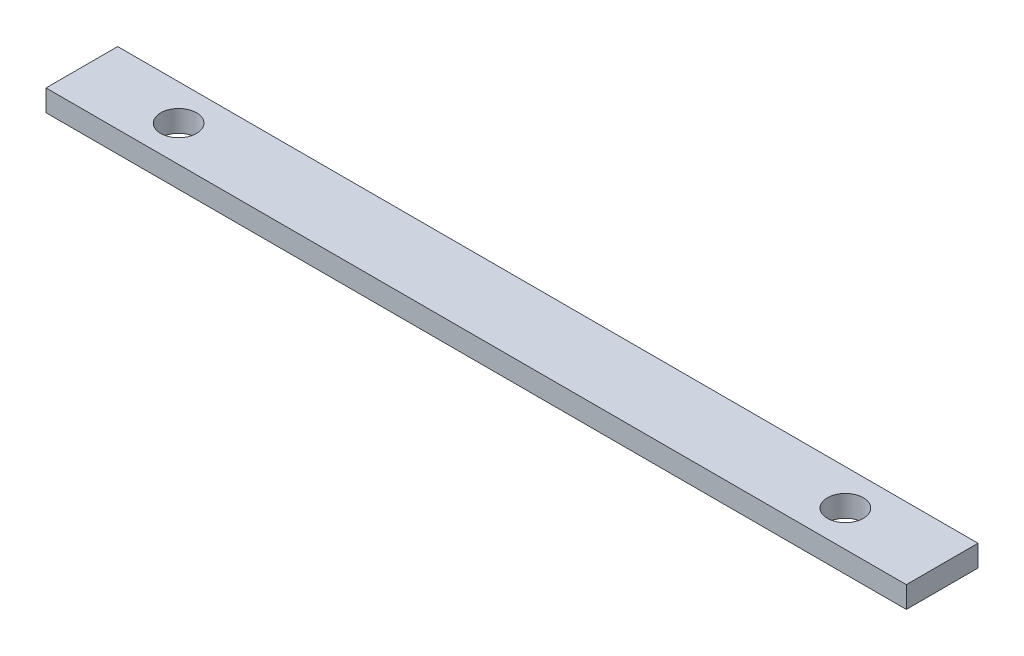
SolidWorks part; units mm, degrees
ref_plane "Front Plane" through (0, 0, 0) normal (0, 0, 1) x (1, 0, 0)
ref_plane "Top Plane" through (0, 0, 0) normal (0, 1, 0) x (1, 0, 0)
ref_plane "Right Plane" through (0, 0, 0) normal (1, 0, 0) x (0, 0, -1)
sketch "Sketch3" plane through (0, 0, 0) normal (0, 1, 0) x (1, 0, 0)
  line L1 (-60, -5) -> (60, -5)
  line L2 (-60, -5) -> (-60, 5)
  line L3 (-60, 5) -> (60, 5)
  line L4 (60, -5) -> (60, 5)
  line L5 (-60, -5) -> (60, 5) construction
  line L6 (-60, 5) -> (60, -5) construction
  point P0 (0, 0)
  dimension "D1" = 120
  dimension "D2" = 10
extrude "Boss-Extrude1" add sketch "Sketch3" along normal blind 3
sketch "Sketch5" plane through (0, 0, 0) normal (0, 1, 0) x (1, 0, 0)
  line L0 (-64.2904, 0) -> (64.0944, 0) construction
  line L1 (0, 30.7056) -> (0, -26.5382) construction
  circle A0 centre (-46.5, 0) radius 2.5
  circle A1 centre (46.5, 0) radius 2.5
  dimension "D1" = 5
  dimension "D2" = 46.5
extrude "Cut-Extrude1" cut sketch "Sketch5" along normal up to surface (3 mm away) up to face at (0, 3, 0)
